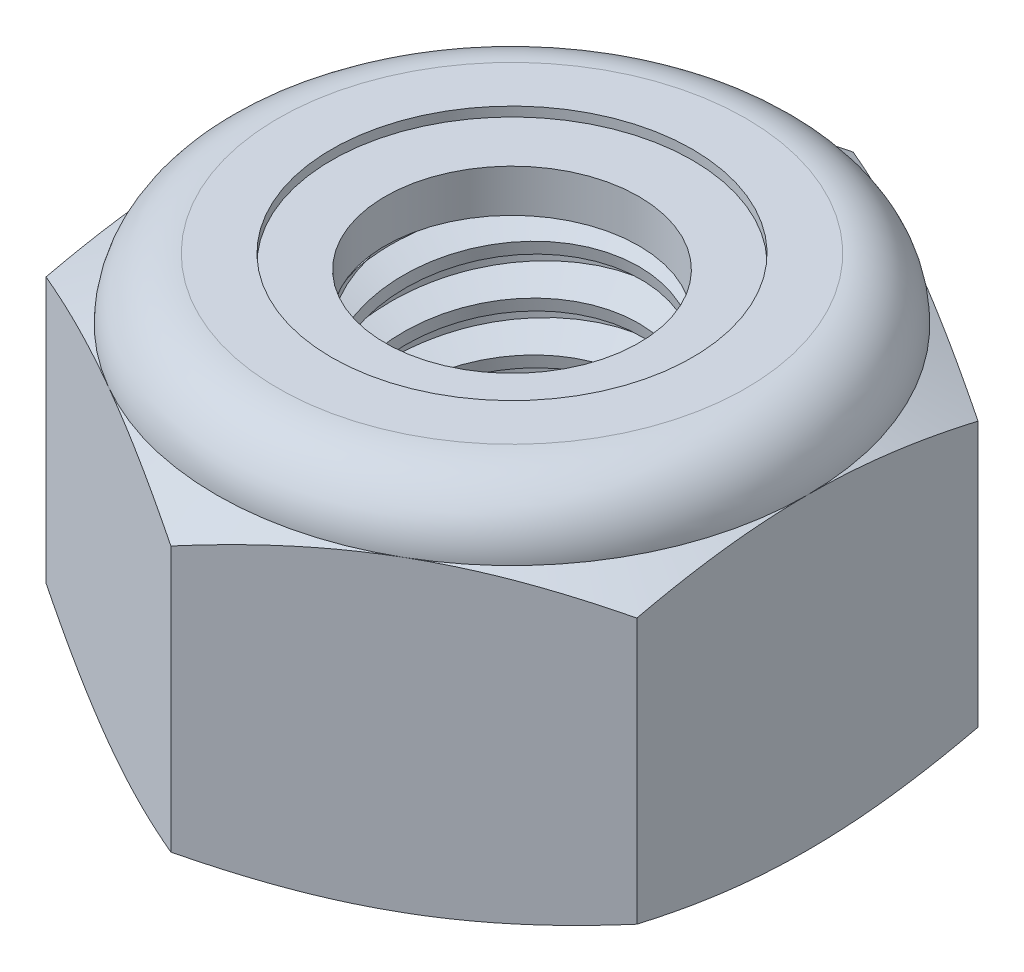
SolidWorks part; units mm, degrees
material "Chrome Stainless Steel"
ref_plane "Front" through (0, 0, 0) normal (0, 0, 1) x (1, 0, 0)
ref_plane "Top" through (0, 0, 0) normal (0, 1, 0) x (1, 0, 0)
ref_plane "Right" through (0, 0, 0) normal (1, 0, 0) x (0, 0, -1)
sketch "Sketch1" plane through (0, 0, 0) normal (0, 1, 0) x (1, 0, 0)
  line L1 (0, 5.4993) -> (-4.7625, 2.7496)
  line L2 (-4.7625, 2.7496) -> (-4.7625, -2.7496)
  line L3 (-4.7625, -2.7496) -> (0, -5.4993)
  line L4 (0, -5.4993) -> (4.7625, -2.7496)
  line L5 (4.7625, -2.7496) -> (4.7625, 2.7496)
  line L6 (4.7625, 2.7496) -> (0, 5.4993)
  circle A0 centre (0, 0) radius 4.7625 construction
  dimension "Hex Flats" = 9.525
extrude "Extrude1" add sketch "Sketch1" along normal blind 5.9531
sketch "Sketch2" plane through (0, 0, 0) normal (1, 0, 0) x (0, 0, -1)
  line L0 (-2.413, 0) -> (-2.413, 5.9531) construction
  line L1 (0, 0) -> (2.413, 0)
  line L2 (0, 0) -> (0, 5.9531)
  line L3 (0, 5.9531) -> (2.413, 5.9531)
  line L4 (2.413, 0) -> (2.413, 5.9531)
  line L5 (-2.7496, 5.9531) -> (2.7496, 5.9531) construction
  line L7 (0, -2.413) -> (0, 0) construction
  dimension "Thread Dia" = 4.826
revolve "Revolve1" add sketch "Sketch2" angle 360 about L7
sketch "Sketch3" plane through (0, 0, 0) normal (1, 0, 0) x (0, 0, -1)
  line L0 (2.413, 5.9531) -> (-2.413, 5.9531) construction
  line L1 (-2.413, 5.9531) -> (-2.413, 5.1594) construction
  line L2 (-2.413, 5.1594) -> (2.413, 5.9531) construction
  line L3 (2.413, 5.9531) -> (2.4291, 5.8552) construction
  line L4 (2.4291, 5.8552) -> (2.5418, 5.1699)
  line L5 (2.5418, 5.1699) -> (2.0776, 5.3449)
  line L6 (2.0776, 5.3449) -> (2.0454, 5.5407)
  line L7 (2.0454, 5.5407) -> (2.4291, 5.8552)
  line L8 (2.0615, 5.4428) -> (2.4855, 5.5126) construction
  line L9 (2.413, 5.9531) -> (2.413, 5.5006) construction
  line L10 (2.413, 5.5006) -> (-2.413, 4.7069) construction
  line L11 (-2.413, 4.7069) -> (-2.413, 5.1594) construction
  line L12 (-0.1397, 5.9531) -> (0.1397, 4.2544) construction
  line L13 (-2.413, 0) -> (-2.413, 5.9531) construction
  line L14 (0, 5.9531) -> (2.413, 5.9531) construction
  line L15 (2.413, 0) -> (2.413, 5.9531) construction
  point P13 (0, 5.1038)
  dimension "D1" = 0.0992
  dimension "D2" = 0.1984
  dimension "Thread Pitch" = 0.7937
  dimension "D4" = 60
  dimension "D5" = 0.7937
revolve "Cut-Revolve1" cut sketch "Sketch3" angle 360 about L12
pattern_linear "LPattern1" count 8 spacing 0.7937 along (0, -1, 0) count 2 spacing 0.7937 along (0, 1, 0) of "Cut-Revolve1"
sketch "Sketch4" plane through (0, 0, 0) normal (1, 0, 0) x (0, 0, -1)
  line L0 (0, 5.9531) -> (2.413, 5.9531)
  line L1 (2.413, 5.9531) -> (2.0454, 5.7817)
  line L2 (2.0454, 5.7817) -> (2.0454, 0.1714)
  line L3 (2.0454, 0.1714) -> (2.413, 0)
  line L4 (2.413, 0) -> (0, 0)
  line L5 (0, 0) -> (0, 5.9531)
  line L6 (2.413, 0) -> (2.413, 5.9531) construction
  line L7 (0, 5.9531) -> (2.413, 5.9531) construction
  line L8 (0, 0) -> (2.413, 0) construction
  line L9 (0, 0) -> (0, 5.9531) construction
  line L10 (0, 5.9531) -> (0, 6.3587) construction
  dimension "D1" = 25
revolve "Cut-Revolve2" cut sketch "Sketch4" angle 360 about L10
combine bodies "Combine1" operation type subtract main body 112 bodies to subtract 111
sketch "Sketch5" plane through (0, 0, 0) normal (1, 0, 0) x (0, 0, -1)
  line L0 (0, 0) -> (4.7625, 0)
  line L1 (4.7625, 0) -> (5.4993, 0.3436)
  line L2 (5.4993, 0.3436) -> (5.4993, 4.6174)
  line L3 (5.4993, 4.6174) -> (4.7625, 4.9609)
  line L4 (3.7703, 5.9531) -> (3.7703, 7.2231)
  line L5 (3.7703, 7.2231) -> (6.7693, 7.2231)
  line L6 (6.7693, 7.2231) -> (6.7693, -1.27)
  line L7 (6.7693, -1.27) -> (0, -1.27)
  line L8 (0, -1.27) -> (0, 0)
  line L9 (4.7625, 4.9609) -> (4.7625, 0) construction
  line L10 (0, 0) -> (2.413, 0) construction
  line L13 (5.4993, 2.4805) -> (6.7693, 2.4805) construction
  line L14 (5.4993, 5.9531) -> (5.4993, 0) construction
  line L15 (0, 0) -> (0, 7.2231) construction
  line L20 (0, 7.2231) -> (3.7703, 7.2231) construction
  line L22 (0, 5.9531) -> (2.413, 5.9531) construction
  arc A0 (4.7625, 4.9609) -> (3.7703, 5.9531) centre (3.7703, 4.9609) ccw
  dimension "D1" = 25
  dimension "D2" = 1.27
  dimension "D3" = 5.9531
  dimension "D4" = 0.9922
revolve "Cut-Revolve3" cut sketch "Sketch5" angle 360 about L15
sketch "Sketch6" plane through (0, 0, 0) normal (1, 0, 0) x (0, 0, -1)
  line L0 (0, 4.9609) -> (4.6101, 4.9609)
  line L1 (3.7703, 5.8007) -> (2.9079, 5.8007)
  line L2 (0, 7.2231) -> (0, 4.9609)
  line L3 (2.9079, 7.2231) -> (0, 7.2231)
  line L4 (0, 7.2231) -> (3.7703, 7.2231) construction
  line L5 (0, 0) -> (0, 7.2231) construction
  line L6 (0, 7.2231) -> (0, 44.323) construction
  line L7 (2.9079, 5.8007) -> (2.9079, 7.2231)
  line L8 (3.7703, 5.9531) -> (3.7703, 5.8007) construction
  line L9 (2.9079, 5.8007) -> (2.0454, 5.8007) construction
  line L10 (2.0454, 5.8007) -> (2.0454, 5.7817) construction
  arc A0 (4.6101, 4.9609) -> (3.7703, 5.8007) centre (3.7703, 4.9609) ccw
  arc A1 (4.7625, 4.9609) -> (3.7703, 5.9531) centre (3.7703, 4.9609) ccw construction
  dimension "D1" = 0.1524
revolve "Cut-Revolve4" cut sketch "Sketch6" angle 360 about L6
sketch "Sketch7" plane through (0, 0, 0) normal (1, 0, 0) x (0, 0, -1)
  line L0 (2.0454, 5.0371) -> (4.5301, 5.0371)
  line L1 (3.7703, 5.7245) -> (2.0454, 5.7245)
  line L2 (2.0454, 5.7245) -> (2.0454, 5.0371)
  line L3 (2.0454, 5.0371) -> (0, 5.0371) construction
  line L4 (0, 5.0371) -> (0, 5.7245) construction
  line L5 (0, 5.7245) -> (2.0454, 5.7245) construction
  line L6 (2.0454, 5.0371) -> (2.0454, 4.9609) construction
  line L7 (0, 4.9609) -> (4.6101, 4.9609) construction
  line L8 (3.7703, 5.7245) -> (3.7703, 5.8007) construction
  arc A0 (4.5301, 5.0371) -> (3.7703, 5.7245) centre (3.7703, 4.9609) ccw
  arc A2 (4.6101, 4.9609) -> (3.7703, 5.8007) centre (3.7703, 4.9609) ccw construction
  dimension "D1" = 0.0762
revolve "Revolve2" add sketch "Sketch7" angle 360 about L4
equation "\"D1@Sketch3\"=\"Thread Pitch@Sketch3\"/8"
equation "\"D2@Sketch3\"=\"Thread Pitch@Sketch3\"/4"
equation "\"D5@Sketch3\"=\"Thread Pitch@Sketch3\""
equation "\"D4@LPattern1\"=\"Thread Pitch@Sketch3\""
equation "\"D3@LPattern1\"=\"Thread Pitch@Sketch3\""
equation "\"D1@LPattern1\"=\"Height@Extrude1\"/\"Thread Pitch@Sketch3\""
equation "\"D4@Sketch5\"=\"Height@Extrude1\"/6"
